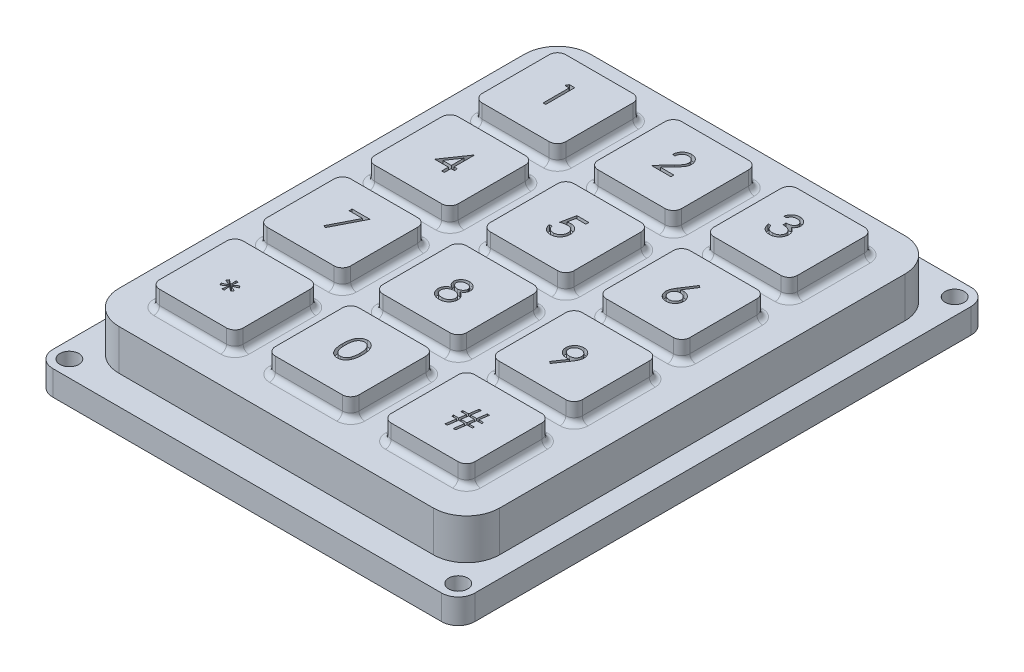
SolidWorks part; units mm, degrees
material "1060 Alloy"
ref_plane "Front Plane" through (0, 0, 0) normal (0, 0, 1) x (1, 0, 0)
ref_plane "Top Plane" through (0, 0, 0) normal (0, 1, 0) x (1, 0, 0)
ref_plane "Right Plane" through (0, 0, 0) normal (1, 0, 0) x (0, 0, -1)
sketch "Sketch1" plane through (0, 0, 0) normal (0, 1, 0) x (1, 0, 0)
  line L1 (23.5, -32) -> (-23.5, -32)
  line L2 (25.5, -30) -> (25.5, 30)
  line L3 (23.5, 32) -> (-23.5, 32)
  line L4 (-25.5, -30) -> (-25.5, 30)
  arc A0 (23.5, -32) -> (25.5, -30) centre (23.5, -30) ccw
  arc A1 (-25.5, -30) -> (-23.5, -32) centre (-23.5, -30) ccw
  arc A2 (-23.5, 32) -> (-25.5, 30) centre (-23.5, 30) ccw
  arc A3 (23.5, 32) -> (25.5, 30) centre (23.5, 30) cw
  point P0 (0, 0)
  dimension "D1" = 2
extrude "Boss-Extrude1" add sketch "Sketch1" along normal blind 3
sketch "Sketch2" plane through (0, 3, 0) normal (0, 1, 0) x (1, 0, 0)
  line L1 (-19, -28.5) -> (19, -28.5)
  line L2 (-23, -24.5) -> (-23, 24.5)
  line L3 (-19, 28.5) -> (19, 28.5)
  line L4 (23, -24.5) -> (23, 24.5)
  line L5 (-23, -28.5) -> (23, 28.5) construction
  line L6 (-23, 28.5) -> (23, -28.5) construction
  arc A0 (23, 24.5) -> (19, 28.5) centre (19, 24.5) ccw
  arc A1 (19, -28.5) -> (23, -24.5) centre (19, -24.5) ccw
  arc A2 (-19, -28.5) -> (-23, -24.5) centre (-19, -24.5) cw
  arc A3 (-19, 28.5) -> (-23, 24.5) centre (-19, 24.5) ccw
  point P0 (0, 0)
  dimension "D1" = 4
extrude "Boss-Extrude2" add sketch "Sketch2" along normal blind 4.9
sketch "Sketch4" plane through (0, 3, 0) normal (0, 1, 0) x (1, 0, 0)
  circle A0 centre (-23.5, 30) radius 1.15
  circle A1 centre (-23.5, -30) radius 1.15
  circle A2 centre (23.5, -30) radius 1.15
  circle A3 centre (23.5, 30) radius 1.15
extrude "Cut-Extrude1" cut sketch "Sketch4" against normal through all
sketch "Sketch5" plane through (0, 7.9, 0) normal (0, 1, 0) x (1, 0, 0)
  line L0 (-4.05, -24.55) -> (4.05, -24.55)
  line L3 (-5.05, -23.55) -> (-5.05, -15.45)
  line L6 (-4.05, -14.45) -> (4.05, -14.45)
  line L7 (5.05, -23.55) -> (5.05, -15.45)
  line L8 (-5.05, -24.55) -> (5.05, -14.45) construction
  line L9 (-5.05, -14.45) -> (5.05, -24.55) construction
  line L10 (9.95, -24.55) -> (18.05, -24.55)
  line L11 (8.95, -23.55) -> (8.95, -15.45)
  line L12 (9.95, -14.45) -> (18.05, -14.45)
  line L13 (-18.05, -24.55) -> (-9.95, -24.55)
  line L14 (-19.05, -23.55) -> (-19.05, -15.45)
  line L15 (-18.05, -14.45) -> (-9.95, -14.45)
  line L16 (-8.95, -23.55) -> (-8.95, -15.45)
  line L17 (-19.05, -24.55) -> (-8.95, -14.45) construction
  line L18 (-19.05, -14.45) -> (-8.95, -24.55) construction
  line L19 (19.05, -23.55) -> (19.05, -15.45)
  line L20 (8.95, -24.55) -> (19.05, -14.45) construction
  line L21 (8.95, -14.45) -> (19.05, -24.55) construction
  line L22 (-4.05, -11.55) -> (4.05, -11.55)
  line L23 (-5.05, -10.55) -> (-5.05, -2.45)
  line L24 (-4.05, -1.45) -> (4.05, -1.45)
  line L25 (5.05, -10.55) -> (5.05, -2.45)
  line L26 (9.95, -11.55) -> (18.05, -11.55)
  line L27 (8.95, -10.55) -> (8.95, -2.45)
  line L28 (9.95, -1.45) -> (18.05, -1.45)
  line L29 (-18.05, -11.55) -> (-9.95, -11.55)
  line L30 (-19.05, -10.55) -> (-19.05, -2.45)
  line L31 (-18.05, -1.45) -> (-9.95, -1.45)
  line L32 (-8.95, -10.55) -> (-8.95, -2.45)
  line L33 (19.05, -10.55) -> (19.05, -2.45)
  line L34 (-5.05, -11.55) -> (5.05, -1.45) construction
  line L35 (-5.05, -1.45) -> (5.05, -11.55) construction
  line L36 (-19.05, -11.55) -> (-8.95, -1.45) construction
  line L37 (-19.05, -1.45) -> (-8.95, -11.55) construction
  line L38 (8.95, -11.55) -> (19.05, -1.45) construction
  line L39 (8.95, -1.45) -> (19.05, -11.55) construction
  line L40 (-4.05, 1.45) -> (4.05, 1.45)
  line L41 (-5.05, 2.45) -> (-5.05, 10.55)
  line L42 (-4.05, 11.55) -> (4.05, 11.55)
  line L43 (5.05, 2.45) -> (5.05, 10.55)
  line L44 (9.95, 1.45) -> (18.05, 1.45)
  line L45 (8.95, 2.45) -> (8.95, 10.55)
  line L46 (9.95, 11.55) -> (18.05, 11.55)
  line L47 (-18.05, 1.45) -> (-9.95, 1.45)
  line L48 (-19.05, 2.45) -> (-19.05, 10.55)
  line L49 (-18.05, 11.55) -> (-9.95, 11.55)
  line L50 (-8.95, 2.45) -> (-8.95, 10.55)
  line L51 (19.05, 2.45) -> (19.05, 10.55)
  line L52 (-5.05, 1.45) -> (5.05, 11.55) construction
  line L53 (-5.05, 11.55) -> (5.05, 1.45) construction
  line L54 (-19.05, 1.45) -> (-8.95, 11.55) construction
  line L55 (-19.05, 11.55) -> (-8.95, 1.45) construction
  line L56 (8.95, 1.45) -> (19.05, 11.55) construction
  line L57 (8.95, 11.55) -> (19.05, 1.45) construction
  line L58 (-4.05, 14.45) -> (4.05, 14.45)
  line L59 (-5.05, 15.45) -> (-5.05, 23.55)
  line L60 (-4.05, 24.55) -> (4.05, 24.55)
  line L61 (5.05, 15.45) -> (5.05, 23.55)
  line L62 (9.95, 14.45) -> (18.05, 14.45)
  line L63 (8.95, 15.45) -> (8.95, 23.55)
  line L64 (9.95, 24.55) -> (18.05, 24.55)
  line L65 (-18.05, 14.45) -> (-9.95, 14.45)
  line L66 (-19.05, 15.45) -> (-19.05, 23.55)
  line L67 (-18.05, 24.55) -> (-9.95, 24.55)
  line L68 (-8.95, 15.45) -> (-8.95, 23.55)
  line L69 (19.05, 15.45) -> (19.05, 23.55)
  line L70 (-5.05, 14.45) -> (5.05, 24.55) construction
  line L71 (-5.05, 24.55) -> (5.05, 14.45) construction
  line L72 (-19.05, 14.45) -> (-8.95, 24.55) construction
  line L73 (-19.05, 24.55) -> (-8.95, 14.45) construction
  line L74 (8.95, 14.45) -> (19.05, 24.55) construction
  line L75 (8.95, 24.55) -> (19.05, 14.45) construction
  arc A0 (-8.95, -23.55) -> (-9.95, -24.55) centre (-9.95, -23.55) cw
  arc A1 (-9.95, -14.45) -> (-8.95, -15.45) centre (-9.95, -15.45) cw
  arc A2 (-18.05, -24.55) -> (-19.05, -23.55) centre (-18.05, -23.55) cw
  arc A3 (-18.05, -14.45) -> (-19.05, -15.45) centre (-18.05, -15.45) ccw
  arc A4 (5.05, -23.55) -> (4.05, -24.55) centre (4.05, -23.55) cw
  arc A5 (4.05, -14.45) -> (5.05, -15.45) centre (4.05, -15.45) cw
  arc A6 (-4.05, -24.55) -> (-5.05, -23.55) centre (-4.05, -23.55) cw
  arc A7 (-4.05, -14.45) -> (-5.05, -15.45) centre (-4.05, -15.45) ccw
  arc A8 (19.05, -23.55) -> (18.05, -24.55) centre (18.05, -23.55) cw
  arc A9 (18.05, -14.45) -> (19.05, -15.45) centre (18.05, -15.45) cw
  arc A10 (9.95, -24.55) -> (8.95, -23.55) centre (9.95, -23.55) cw
  arc A11 (9.95, -14.45) -> (8.95, -15.45) centre (9.95, -15.45) ccw
  arc A12 (-8.95, -10.55) -> (-9.95, -11.55) centre (-9.95, -10.55) cw
  arc A13 (-9.95, -1.45) -> (-8.95, -2.45) centre (-9.95, -2.45) cw
  arc A14 (-18.05, -11.55) -> (-19.05, -10.55) centre (-18.05, -10.55) cw
  arc A15 (-18.05, -1.45) -> (-19.05, -2.45) centre (-18.05, -2.45) ccw
  arc A16 (5.05, -10.55) -> (4.05, -11.55) centre (4.05, -10.55) cw
  arc A17 (4.05, -1.45) -> (5.05, -2.45) centre (4.05, -2.45) cw
  arc A18 (-4.05, -11.55) -> (-5.05, -10.55) centre (-4.05, -10.55) cw
  arc A19 (-4.05, -1.45) -> (-5.05, -2.45) centre (-4.05, -2.45) ccw
  arc A20 (19.05, -10.55) -> (18.05, -11.55) centre (18.05, -10.55) cw
  arc A21 (18.05, -1.45) -> (19.05, -2.45) centre (18.05, -2.45) cw
  arc A22 (9.95, -11.55) -> (8.95, -10.55) centre (9.95, -10.55) cw
  arc A23 (9.95, -1.45) -> (8.95, -2.45) centre (9.95, -2.45) ccw
  arc A24 (-8.95, 2.45) -> (-9.95, 1.45) centre (-9.95, 2.45) cw
  arc A25 (-9.95, 11.55) -> (-8.95, 10.55) centre (-9.95, 10.55) cw
  arc A26 (-18.05, 1.45) -> (-19.05, 2.45) centre (-18.05, 2.45) cw
  arc A27 (-18.05, 11.55) -> (-19.05, 10.55) centre (-18.05, 10.55) ccw
  arc A28 (5.05, 2.45) -> (4.05, 1.45) centre (4.05, 2.45) cw
  arc A29 (4.05, 11.55) -> (5.05, 10.55) centre (4.05, 10.55) cw
  arc A30 (-4.05, 1.45) -> (-5.05, 2.45) centre (-4.05, 2.45) cw
  arc A31 (-4.05, 11.55) -> (-5.05, 10.55) centre (-4.05, 10.55) ccw
  arc A32 (19.05, 2.45) -> (18.05, 1.45) centre (18.05, 2.45) cw
  arc A33 (18.05, 11.55) -> (19.05, 10.55) centre (18.05, 10.55) cw
  arc A34 (9.95, 1.45) -> (8.95, 2.45) centre (9.95, 2.45) cw
  arc A35 (9.95, 11.55) -> (8.95, 10.55) centre (9.95, 10.55) ccw
  arc A36 (-8.95, 15.45) -> (-9.95, 14.45) centre (-9.95, 15.45) cw
  arc A37 (-9.95, 24.55) -> (-8.95, 23.55) centre (-9.95, 23.55) cw
  arc A38 (-18.05, 14.45) -> (-19.05, 15.45) centre (-18.05, 15.45) cw
  arc A39 (-18.05, 24.55) -> (-19.05, 23.55) centre (-18.05, 23.55) ccw
  arc A40 (5.05, 15.45) -> (4.05, 14.45) centre (4.05, 15.45) cw
  arc A41 (4.05, 24.55) -> (5.05, 23.55) centre (4.05, 23.55) cw
  arc A42 (-4.05, 14.45) -> (-5.05, 15.45) centre (-4.05, 15.45) cw
  arc A43 (-4.05, 24.55) -> (-5.05, 23.55) centre (-4.05, 23.55) ccw
  arc A44 (19.05, 15.45) -> (18.05, 14.45) centre (18.05, 15.45) cw
  arc A45 (18.05, 24.55) -> (19.05, 23.55) centre (18.05, 23.55) cw
  arc A46 (9.95, 14.45) -> (8.95, 15.45) centre (9.95, 15.45) cw
  arc A47 (9.95, 24.55) -> (8.95, 23.55) centre (9.95, 23.55) ccw
  dimension "D1" = 3
  dimension "D2" = 4
extrude "Boss-Extrude4" add sketch "Sketch5" along normal blind 2.4
fillet "Fillet1" radius 0.7 96 edges at (18.7571, 7.9, 24.2571) (14, 7.9, 24.55) (9.2429, 7.9, 24.2571) (8.95, 7.9, 19.5) (9.2429, 7.9, 14.7429) (14, 7.9, 14.45) (18.7571, 7.9, 14.7429) (4.7571, 7.9, 24.2571) (0, 7.9, 24.55) (-4.7571, 7.9, 24.2571) (-5.05, 7.9, 19.5) (-4.7571, 7.9, 14.7429) (0, 7.9, 14.45) (4.7571, 7.9, 14.7429) (-9.2429, 7.9, 24.2571) (-14, 7.9, 24.55) (-18.7571, 7.9, 24.2571) (-19.05, 7.9, 19.5) (-18.7571, 7.9, 14.7429) (-14, 7.9, 14.45) (-9.2429, 7.9, 14.7429) (18.7571, 7.9, 11.2571) (14, 7.9, 11.55) (9.2429, 7.9, 11.2571) (8.95, 7.9, 6.5) (9.2429, 7.9, 1.7429) (14, 7.9, 1.45) (18.7571, 7.9, 1.7429) (4.7571, 7.9, 11.2571) (0, 7.9, 11.55) (-4.7571, 7.9, 11.2571) (-5.05, 7.9, 6.5) (-4.7571, 7.9, 1.7429) (0, 7.9, 1.45) (4.7571, 7.9, 1.7429) (-9.2429, 7.9, 11.2571) (-14, 7.9, 11.55) (-18.7571, 7.9, 11.2571) (-19.05, 7.9, 6.5) (-18.7571, 7.9, 1.7429) (-14, 7.9, 1.45) (-9.2429, 7.9, 1.7429) (-9.2429, 7.9, -1.7429) (-14, 7.9, -1.45) (-18.7571, 7.9, -1.7429) (-19.05, 7.9, -6.5) (-18.7571, 7.9, -11.2571) (-14, 7.9, -11.55) (-9.2429, 7.9, -11.2571) (4.7571, 7.9, -1.7429) (0, 7.9, -1.45) (-4.7571, 7.9, -1.7429) (-5.05, 7.9, -6.5) (-4.7571, 7.9, -11.2571) (0, 7.9, -11.55) (4.7571, 7.9, -11.2571) (18.7571, 7.9, -1.7429) (14, 7.9, -1.45) (9.2429, 7.9, -1.7429) (8.95, 7.9, -6.5) (9.2429, 7.9, -11.2571) (14, 7.9, -11.55) (18.7571, 7.9, -11.2571) (18.7571, 7.9, -14.7429) (14, 7.9, -14.45) (9.2429, 7.9, -14.7429) (8.95, 7.9, -19.5) (9.2429, 7.9, -24.2571) (14, 7.9, -24.55) (18.7571, 7.9, -24.2571) (4.7571, 7.9, -14.7429) (0, 7.9, -14.45) (-4.7571, 7.9, -14.7429) (-5.05, 7.9, -19.5) (-4.7571, 7.9, -24.2571) (0, 7.9, -24.55) (4.7571, 7.9, -24.2571) (-9.2429, 7.9, -14.7429) (-14, 7.9, -14.45) (-18.7571, 7.9, -14.7429) (-19.05, 7.9, -19.5) (-18.7571, 7.9, -24.2571) (-14, 7.9, -24.55) (-9.2429, 7.9, -24.2571) (19.05, 7.9, 19.5) (5.05, 7.9, 19.5) (-8.95, 7.9, 19.5) (19.05, 7.9, 6.5) (5.05, 7.9, 6.5) (-8.95, 7.9, 6.5) (-8.95, 7.9, -6.5) (5.05, 7.9, -6.5) (19.05, 7.9, -6.5) (19.05, 7.9, -19.5) (5.05, 7.9, -19.5) (-8.95, 7.9, -19.5)
sketch "Sketch6" plane through (0, 3, 0) normal (0, 1, 0) x (1, 0, 0)
  line L2 (-3, 32) -> (-3, 28.8207)
  line L3 (3, 32) -> (3, 28.8207)
  line L4 (-3, 28.8207) -> (3, 28.8207)
  line L5 (-3, 32) -> (0, 37.9553)
  line L6 (0, 37.9553) -> (3, 32)
extrude "Cut-Extrude2" cut sketch "Sketch6" against normal through all
fillet "Fillet2" radius 2 2 edges at (3, 1.5, -28.8207) (-3, 1.5, -28.8207)
sketch "Sketch7" plane through (0, 10.3, 0) normal (0, 1, 0) x (1, 0, 0)
  text T0 "1"
  text T1 "2"
  text T2 "3"
  text T3 "4"
  text T4 "5"
  text T5 "6"
  text T6 "7"
  text T7 "8"
  text T8 "9"
  text T9 "0"
  text T10 "#"
  text T11 "*"
extrude "Cut-Extrude3" cut sketch "Sketch7" against normal blind 0.7
